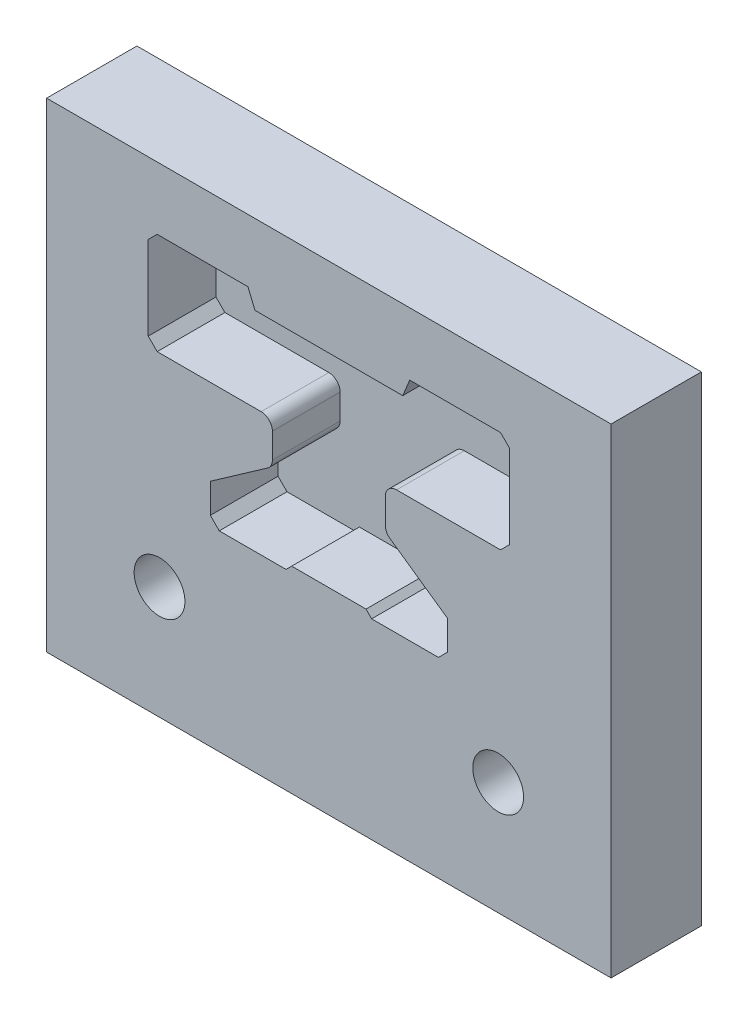
SolidWorks part; units mm, degrees
material "ABS"
ref_plane "Front Plane" through (0, 0, 0) normal (0, 0, 1) x (1, 0, 0)
ref_plane "Top Plane" through (0, 0, 0) normal (0, 1, 0) x (1, 0, 0)
ref_plane "Right Plane" through (0, 0, 0) normal (1, 0, 0) x (0, 0, -1)
sketch "Sketch1" plane through (0, 0, 0) normal (0, 0, 1) x (1, 0, 0)
  line L1 (-25, 21.25) -> (25, 21.25)
  line L2 (-25, 21.25) -> (-25, -21.25)
  line L3 (-25, -21.25) -> (25, -21.25)
  line L4 (25, 21.25) -> (25, -21.25)
  line L5 (-25, 21.25) -> (25, -21.25) construction
  line L6 (-25, -21.25) -> (25, 21.25) construction
  point P0 (0, 0)
  dimension "D1" = 42.5
  dimension "D2" = 50
extrude "Boss-Extrude1" add sketch "Sketch1" along normal blind 8
sketch "Sketch2" plane through (0, 0, 8) normal (0, 0, 1) x (1, 0, 0)
  line L0 (0, -3.6294) -> (0, 21.4196) construction
  line L1 (-3.5, -3.3) -> (3.5, -3.3) construction
  line L2 (3.5, -3.3) -> (3.9999, -3.7999) construction
  line L3 (3.9999, -3.7999) -> (9.4999, -3.7999) construction
  line L4 (9.4999, -3.7999) -> (9.9998, -3.3) construction
  line L5 (9.9998, -3.3) -> (9.9998, -1.151) construction
  line L6 (9.9998, -1.151) -> (5.1396, 2.2522) construction
  line L7 (4.5, 3.4809) -> (4.5, 5.6999) construction
  line L8 (6, 7.1999) -> (15, 7.1999) construction
  line L9 (15, 7.1999) -> (15.4999, 7.6998) construction
  line L10 (15.4999, 7.6998) -> (15.4999, 14.6998) construction
  line L11 (15.4999, 14.6998) -> (15, 15.1998) construction
  line L12 (15, 15.1998) -> (7.5, 15.1998) construction
  line L13 (7.5, 15.1998) -> (6.8785, 13.6994) construction
  line L14 (6.8785, 13.6994) -> (-6.8785, 13.6994) construction
  line L15 (-7.5, 15.1998) -> (-6.8785, 13.6994) construction
  line L16 (-15, 15.1998) -> (-7.5, 15.1998) construction
  line L17 (-15.4999, 14.6998) -> (-15, 15.1998) construction
  line L18 (-15.4999, 7.6998) -> (-15.4999, 14.6998) construction
  line L19 (-15, 7.1999) -> (-15.4999, 7.6998) construction
  line L20 (-6, 7.1999) -> (-15, 7.1999) construction
  line L21 (-4.5, 3.4809) -> (-4.5, 5.6999) construction
  line L22 (-9.9998, -1.151) -> (-5.1396, 2.2522) construction
  line L23 (-9.9998, -3.3) -> (-9.9998, -1.151) construction
  line L24 (-9.4999, -3.7999) -> (-9.9998, -3.3) construction
  line L25 (-3.9999, -3.7999) -> (-9.4999, -3.7999) construction
  line L26 (-3.5, -3.3) -> (-3.9999, -3.7999) construction
  line L53 (0, 21.25) -> (0, -21.25) construction
  line L54 (25, 21.25) -> (-25, 21.25) construction
  line L55 (-25, -21.25) -> (25, -21.25) construction
  line L56 (-25, -3.8) -> (25, -3.8) construction
  line L57 (-25, 21.25) -> (-25, -21.25) construction
  line L58 (25, -21.25) -> (25, 21.25) construction
  line L60 (-3.2929, -3.8) -> (3.2929, -3.8)
  line L61 (3.2929, -3.8) -> (3.7928, -4.2999)
  line L62 (3.7928, -4.2999) -> (9.707, -4.2999)
  line L63 (9.707, -4.2999) -> (10.4998, -3.5071)
  line L64 (10.4998, -3.5071) -> (10.4998, -0.8907)
  line L65 (10.4998, -0.8907) -> (5.4264, 2.6617)
  line L66 (5, 3.4809) -> (5, 5.6999)
  line L67 (6, 6.6999) -> (15.2071, 6.6999)
  line L68 (15.2071, 6.6999) -> (15.9999, 7.4927)
  line L69 (15.9999, 7.4927) -> (15.9999, 14.9069)
  line L70 (15.9999, 14.9069) -> (15.2071, 15.6998)
  line L71 (15.2071, 15.6998) -> (7.1659, 15.6998)
  line L72 (7.1659, 15.6998) -> (6.5444, 14.1994)
  line L73 (6.5444, 14.1994) -> (-6.5444, 14.1994)
  line L74 (-7.1659, 15.6998) -> (-6.5444, 14.1994)
  line L75 (-15.2071, 15.6998) -> (-7.1659, 15.6998)
  line L76 (-15.9999, 14.9069) -> (-15.2071, 15.6998)
  line L77 (-15.9999, 7.4927) -> (-15.9999, 14.9069)
  line L78 (-15.2071, 6.6999) -> (-15.9999, 7.4927)
  line L79 (-6, 6.6999) -> (-15.2071, 6.6999)
  line L80 (-5, 3.4809) -> (-5, 5.6999)
  line L81 (-10.4998, -0.8907) -> (-5.4264, 2.6617)
  line L82 (-10.4998, -3.5071) -> (-10.4998, -0.8907)
  line L83 (-9.707, -4.2999) -> (-10.4998, -3.5071)
  line L84 (-3.7928, -4.2999) -> (-9.707, -4.2999)
  line L85 (-3.2929, -3.8) -> (-3.7928, -4.2999)
  arc A0 (6, 7.1999) -> (4.5, 5.6999) centre (6, 5.6999) ccw construction
  arc A1 (4.5, 3.4809) -> (5.1396, 2.2522) centre (6, 3.4809) ccw construction
  arc A2 (-4.5, 3.4809) -> (-5.1396, 2.2522) centre (-6, 3.4809) cw construction
  arc A3 (-6, 7.1999) -> (-4.5, 5.6999) centre (-6, 5.6999) cw construction
  arc A8 (5, 3.4809) -> (5.4264, 2.6617) centre (6, 3.4809) ccw
  arc A9 (6, 6.6999) -> (5, 5.6999) centre (6, 5.6999) ccw
  arc A10 (-6, 6.6999) -> (-5, 5.6999) centre (-6, 5.6999) cw
  arc A11 (-5, 3.4809) -> (-5.4264, 2.6617) centre (-6, 3.4809) cw
  point P28 (0, 13.6994)
  point P38 (0, -3.3)
  dimension "D6" = 1.5
  dimension "D1" = 3.5
  dimension "D2" = 135
  dimension "D3" = 0.707
  dimension "D4" = 5.5
  dimension "D5" = 2.149
  dimension "D7" = 35
  dimension "D8" = 2.219
  dimension "D9" = 9
  dimension "D10" = 7
  dimension "D11" = 135
  dimension "D12" = 0.707
  dimension "D13" = 112.5
  dimension "D14" = 1.624
  dimension "D15" = 7.5
  dimension "D16" = 6.8785
  dimension "D17" = 25.05
  dimension "D18" = 0.5
extrude "Cut-Extrude1" cut sketch "Sketch2" against normal blind 6
sketch "Sketch3" plane through (0, 0, 8) normal (0, 0, 1) x (1, 0, 0)
  line L0 (-25, -11.25) -> (25, -11.25) construction
  line L1 (-25, 21.25) -> (-25, -21.25) construction
  line L2 (25, -21.25) -> (25, 21.25) construction
  line L3 (-25, -21.25) -> (25, -21.25) construction
  line L4 (0, -21.25) -> (0, 21.25) construction
  line L5 (25, 21.25) -> (-25, 21.25) construction
  circle A0 centre (-15, -11.25) radius 2.25
  circle A1 centre (15, -11.25) radius 2.25
  dimension "D2" = 4.5
  dimension "D1" = 10
  dimension "D3" = 10
extrude "Cut-Extrude2" cut sketch "Sketch3" against normal through all
